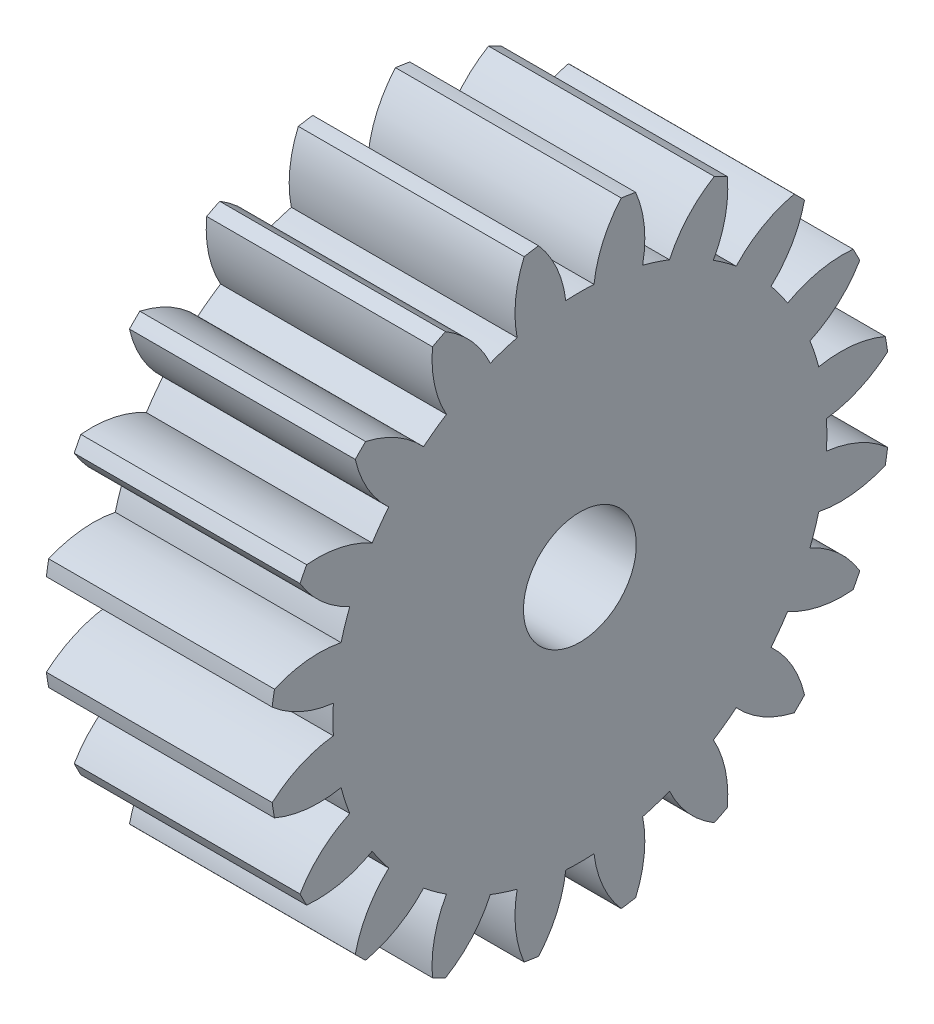
SolidWorks part; units mm, degrees
ref_plane "Plane1" through (0, 0, 0) normal (0, 0, 1) x (1, 0, 0)
ref_plane "Plane2" through (0, 0, 0) normal (0, 1, 0) x (1, 0, 0)
ref_plane "Plane3" through (0, 0, 0) normal (1, 0, 0) x (0, 0, -1)
other "Configuration Table"
sketch "HoldingSke" plane through (0, 0, 0) normal (0, 1, 0) x (1, 0, 0)
  line L0 (0, 0) -> (0.9397, -0.342)
  line L1 (-15, 0) -> (100, 0) construction
  line L2 (0, 0) -> (-2.1039, 2.3779)
  line L3 (0, 0) -> (-11.863, 4.5341)
  line L4 (0, 0) -> (8.1152, 2.9537)
  line L5 (0, 0) -> (-46.8476, -17.4728)
  line L6 (0, 0) -> (-6.6317, -4.4744)
  line L7 (-2.1039, 2.3779) -> (8.6586, 51.2059)
  line L8 (-76.2, 54.61) -> (-75.5, 54.61)
  line L9 (-71.009, 38.7566) -> (-53.1078, 45.2721)
  line L10 (-76.2, 71.12) -> (104.1128, 71.12)
  line L11 (0, 0) -> (-8, 0)
  line L12 (-76.2, 101.6) -> (-76.162, 101.6)
  line L13 (24.9733, 27.94) -> (52.9518, 28.4284)
  line L14 (24.9733, 27.94) -> (24.9743, 27.94)
  line L15 (24.9733, 27.94) -> (100.4006, 29.5858)
  line L16 (-63.627, -1) -> (-12.827, -1)
  circle A0 centre (0, 0) radius 2
  circle A1 centre (0, 0) radius 8.749
  circle A2 centre (0, 0) radius 37.5
  circle A3 centre (0, 0) radius 2
  dimension "MHD" = 17.498
  dimension "Hub_dia" = 75
  dimension "Bore" = 4
  dimension "MBD" = 4
  dimension "Num_teeth" = 20
  dimension "Pitch" = 1
  dimension "Overall_len" = 50
  dimension "Show_teeth" = 20
  dimension "Thickness" = 8
  dimension "OAL" = 50.0001
  dimension "T_dim" = 0.7
  dimension "Ap" = 20
  dimension "H" = 19.05
  dimension "Pitch_radius" = 180.3128
  dimension "Width" = 8
  dimension "Backlash" = 0.038
  dimension "Addendum_fac" = 1
  dimension "Dedendum_fac" = 1.25
  dimension "Clearance_fac" = 0.25
  dimension "Dedendum_add" = 0.001
  dimension "Module" = 1
sketch "BasProSke" plane through (0, 0, 0) normal (0, 1, 0) x (1, 0, 0)
  line L0 (-10, 0) -> (60, 0) construction
  line L1 (0, 0) -> (0, 11)
  line L2 (0, 0) -> (8, 0)
  line L3 (8, 0) -> (8, 11)
  line L4 (8, 11) -> (0, 11)
  dimension "Thickness" = 8
  dimension "Diameter" = 22
revolve "Base-Revolve" add sketch "BasProSke" angle 360 about L0
sketch "TooCutSke" plane through (0, 0, 0) normal (1, 0, 0) x (0, 0, -1)
  line L1 (0, 0) -> (0, 107) construction
  line L2 (0, 0) -> (-0.8511, 9.9637) construction
  line L3 (0, 0) -> (-3.1206, 19.7028) construction
  line L4 (-0.8511, 9.9637) -> (-1.5603, 9.8514) construction
  arc A0 (0.4999, 8.7347) -> (-0.4999, 8.7347) centre (0, 0) ccw
  arc A1 (1.4852, 10.9249) -> (-1.4852, 10.9249) centre (0, 0) ccw
  circle A2 centre (0, 0) radius 10 construction
  circle A3 centre (0, 0) radius 9.3969 construction
  arc A4 (-0.4999, 8.7347) -> (-1.4852, 10.9249) centre (-4.4722, 8.2645) ccw
  arc A5 (1.4852, 10.9249) -> (0.4999, 8.7347) centre (4.4722, 8.2645) ccw
  dimension "Root_dia" = 17.498
  dimension "Overcut_dia" = 22.0508
  dimension "Pitch_dia" = 20
  dimension "Base_dia" = 18.7939
  dimension "Flank_rad" = 4
  dimension "Half_ang" = 9
  dimension "Half_CT" = 0.7181
extrude "ToothCut" cut sketch "TooCutSke" along normal through all
fillet "Breaks" [suppressed] radius 0.02
fillet "RootFillets" [suppressed] radius 0.251
pattern_circular "TeethCuts" count 20 every 18 about axis through (-10, 0, 0) along (1, 0, 0) of "ToothCut", "RootFillets", "Breaks"
sketch "HubNeaOneSke" plane through (0, 0, 0) normal (-1, 0, 0) x (0, 0, 1)
  circle A0 centre (0, 0) radius 8.749
  dimension "Diameter" = 17.498
extrude "HubNearOne" [suppressed] add sketch "HubNeaOneSke" along normal blind 42.0001
sketch "HubNeaBotSke" plane through (0, 0, 0) normal (-1, 0, 0) x (0, 0, 1)
  circle A0 centre (0, 0) radius 8.749
  dimension "Diameter" = 17.498
extrude "HubNearBoth" [suppressed] add sketch "HubNeaBotSke" along normal blind 21
ref_plane "FarPln" through (8, 0, 0) normal (1, 0, 0) x (0, 0, -1)
sketch "HubFarSke" plane through (8, 0, 0) normal (1, 0, 0) x (0, 0, -1)
  circle A0 centre (0, 0) radius 8.749
  dimension "Diameter" = 17.498
extrude "HubFar" [suppressed] add sketch "HubFarSke" along normal blind 21
sketch "BorSke" plane through (0, 0, 0) normal (1, 0, 0) x (0, 0, -1)
  circle A0 centre (0, 0) radius 2
  dimension "Diameter" = 4
extrude "Bore" cut sketch "BorSke" along normal mid plane 100.0001
sketch "KeySke" plane through (0, 0, 0) normal (1, 0, 0) x (0, 0, -1)
  line L0 (-0.8, 0) -> (-0.8, 2.7)
  line L1 (-0.8, 2.7) -> (0.8, 2.7)
  line L2 (0.8, 2.7) -> (0.8, 0)
  line L3 (0, 0) -> (0, 34) construction
  line L4 (-0.8, 0) -> (0.8, 0)
  dimension "Offset" = 2.7
  dimension "Width" = 1.6
extrude "Keyway" [suppressed] cut sketch "KeySke" along normal mid plane 100.0001
pattern_circular "Keyway2" [suppressed] count 2 every 90 about axis through (-10, 0, 0) along (1, 0, 0)
equation "' \"Module@HoldingSke\" = 6.35"
equation "' \"Num_teeth@HoldingSke\" = 12"
equation "' \"Ap@HoldingSke\" =  20"
equation "' \"Ap@HoldingSke\" = 20"
equation "' \"Width@HoldingSke\" = 0.5 * 25.4"
equation "' \"Hub_dia@HoldingSke\"= 1 * 25.4"
equation "' \"Hub_dia@HoldingSke\" = 1 * 25.4"
equation "' \"Overall_len@HoldingSke\" = 1.0 * 25.4"
equation "' \"Bore@HoldingSke\" = 0.75 * 25.4"
equation "' \"T_dim@HoldingSke\" = 0.1 * 25.4"
equation "' \"Width@KeySke\" = 0.25 * 25.4"
equation "' \"Show_teeth@HoldingSke\" = 13"
equation "' \"Backlash@HoldingSke\" = 0.009 * 25.4"
equation "' \"Addendum_fac@HoldingSke\" = 1.0"
equation "' \"Dedendum_fac@HoldingSke\" = 1.25"
equation "' \"Dedendum_add@HoldingSke\" = 0.00005 * 25.4"
equation "' \"Clearance_fac@HoldingSke\" = 0.25"
equation "\"Pitch@HoldingSke\" = 1 / \"Module@HoldingSke\""
equation "\"Overcut_dia@TooCutSke\" = (\"Num_teeth@HoldingSke\" + 2 * \"Addendum_fac@HoldingSke\") / \"Pitch@HoldingSke\" + 0.002 * 25.4"
equation "\"Pitch_dia@TooCutSke\" = \"Num_teeth@HoldingSke\" / \"Pitch@HoldingSke\""
equation "\"Base_dia@TooCutSke\" = \"Num_teeth@HoldingSke\" / \"Pitch@HoldingSke\" * cos((\"Ap@HoldingSke\"  * 3.14159265 / 180))"
equation "\"Root_dia@TooCutSke\" = (\"Num_teeth@HoldingSke\" + 2) / \"Pitch@HoldingSke\" - 2 * (\"Addendum_fac@HoldingSke\" + \"Dedendum_fac@HoldingSke\") / \"Pitch@HoldingSke\" - \"Dedendum_add@HoldingSke\" * 2"
equation "\"Half_ang@TooCutSke\" = 180 / \"Num_teeth@HoldingSke\""
equation "\"Half_CT@TooCutSke\" = \"Num_teeth@HoldingSke\" / \"Pitch@HoldingSke\" * sin((3.14159265 / 2 / \"Num_teeth@HoldingSke\")) / 2 - 7 * \"Backlash@HoldingSke\" / 4"
equation "\"Flank_rad@TooCutSke\" = \"Num_teeth@HoldingSke\" / \"Pitch@HoldingSke\" / 5"
equation "\"Radius@RootFillets\" = \"Clearance_fac@HoldingSke\" / \"Pitch@HoldingSke\" + \"Dedendum_add@HoldingSke\""
equation "\"Break_rad@Breaks\" = 0.02 / \"Pitch@HoldingSke\""
equation "\"Thickness@HoldingSke\" = \"Width@HoldingSke\""
equation "\"OAL@HoldingSke\" = \"Thickness@HoldingSke\""
equation "\"MHD@HoldingSke\" = (\"Num_teeth@HoldingSke\" + 2) / \"Pitch@HoldingSke\" - 2 * (\"Addendum_fac@HoldingSke\" + \"Dedendum_fac@HoldingSke\")  / \"Pitch@HoldingSke\" - \"Dedendum_add@HoldingSke\" * 2"
equation "\"MBD@HoldingSke\" = (\"Num_teeth@HoldingSke\" + 2) / \"Pitch@HoldingSke\" - 2 * (\"Addendum_fac@HoldingSke\" + \"Dedendum_fac@HoldingSke\")  / \"Pitch@HoldingSke\" - \"Dedendum_add@HoldingSke\" * 2 - 0.002 * 25.4"
equation "\"MHD@HoldingSke\" = ((sgn( \"MHD@HoldingSke\" - \"Hub_dia@HoldingSke\" )-1)*( \"MHD@HoldingSke\" - \"Hub_dia@HoldingSke\" ))/-2+ \"Hub_dia@HoldingSke\""
equation "\"MBD@HoldingSke\" = ((sgn( \"MBD@HoldingSke\" - \"Bore@HoldingSke\" )-1)*( \"MBD@HoldingSke\" - \"Bore@HoldingSke\" ))/-2+ \"Bore@HoldingSke\""
equation "\"OAL@HoldingSke\" = ((sgn( \"OAL@HoldingSke\" - \"Overall_len@HoldingSke\" )+1)*( \"OAL@HoldingSke\" - \"Overall_len@HoldingSke\" ))/2 + \"Overall_len@HoldingSke\" + 0.000002 * 25.4"
equation "\"Num_teeth@TeethCuts\" = int( \"Show_teeth@HoldingSke\" ) + 1"
equation "\"Num_teeth@TeethCuts\" = ((sgn( \"Num_teeth@TeethCuts\" - \"Num_teeth@HoldingSke\" )-1)*( \"Num_teeth@TeethCuts\" - \"Num_teeth@HoldingSke\" ))/-2+ \"Num_teeth@HoldingSke\""
equation "\"Num_teeth@TeethCuts\" = ((sgn( \"Num_teeth@TeethCuts\" - 2.0)+1)*( \"Num_teeth@TeethCuts\" - 2.0))/2 +2.0"
equation "\"Angle@TeethCuts\" = 360.0 / \"Num_teeth@HoldingSke\""
equation "\"Diameter@BasProSke\" = (\"Num_teeth@HoldingSke\" + 2 * \"Addendum_fac@HoldingSke\") / \"Pitch@HoldingSke\""
equation "\"Thickness@BasProSke\"  = \"Thickness@HoldingSke\""
equation "' \"Fillet_rad@BasProSke\" =  \"Thickness@HoldingSke\" * 0.05"
equation "' \"Fillet_rad@BasProSke\" = \"Thickness@HoldingSke\" * 0.05"
equation "\"MHD@HoldingSke\" = ((sgn( \"MHD@HoldingSke\" - \"Root_dia@TooCutSke\" )-1)*( \"MHD@HoldingSke\" - \"Root_dia@TooCutSke\" ))/-2+ \"Root_dia@TooCutSke\""
equation "\"Diameter@HubNeaOneSke\" = \"MHD@HoldingSke\""
equation "\"Length@HubNearOne\" = \"OAL@HoldingSke\" - \"Thickness@BasProSke\""
equation "\"Diameter@HubNeaBotSke\" = \"MHD@HoldingSke\""
equation "\"Length@HubNearBoth\" = ( \"OAL@HoldingSke\" - \"Thickness@BasProSke\" ) / 2.0"
equation "\"Thickness@FarPln\" = \"Thickness@BasProSke\""
equation "\"Diameter@HubFarSke\" = \"MHD@HoldingSke\""
equation "\"Length@HubFar\" = ( \"OAL@HoldingSke\" - \"Thickness@BasProSke\" ) / 2.0"
equation "\"Diameter@BorSke\" = \"MBD@HoldingSke\""
equation "\"D1@Bore\" = \"OAL@HoldingSke\" * 2.0"
equation "\"D1@Keyway\" = \"OAL@HoldingSke\" * 2.0"
equation "\"Offset@KeySke\" = \"T_dim@HoldingSke\" + \"MBD@HoldingSke\" / 2.0"
